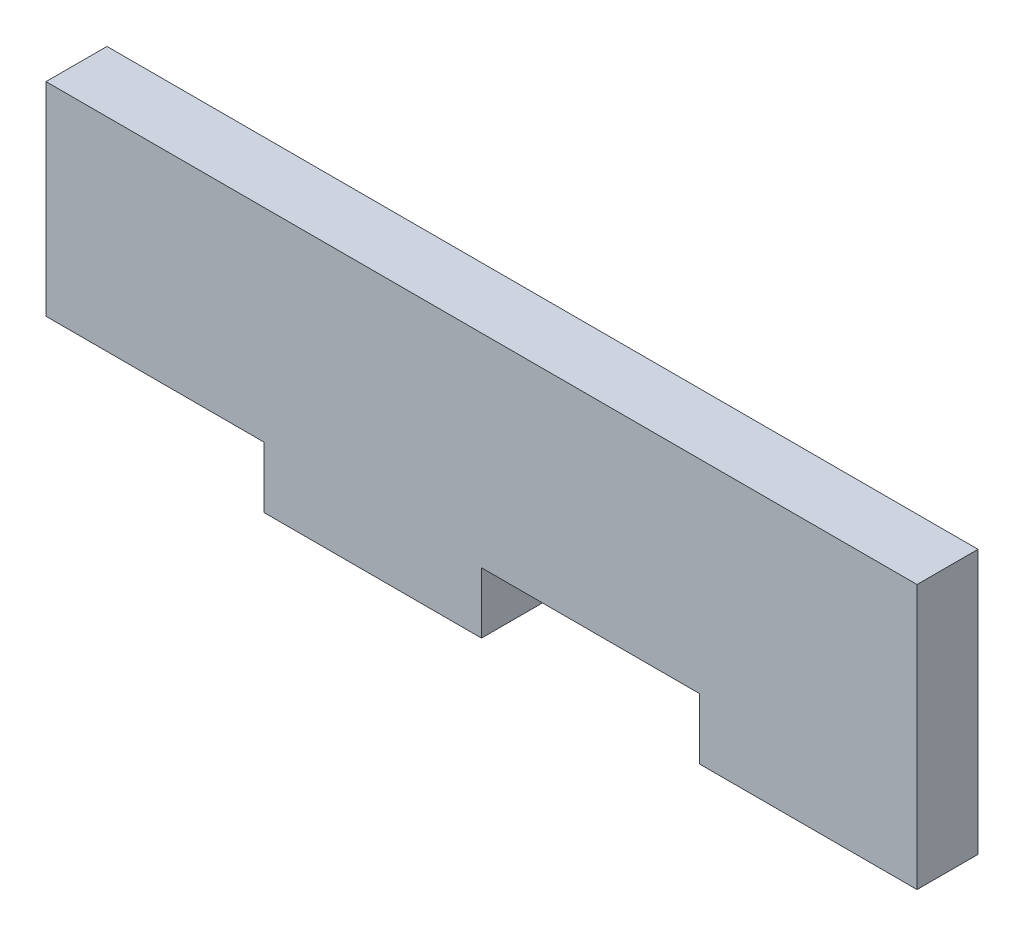
SolidWorks part; units mm, degrees
ref_plane "Front Plane" through (0, 0, 0) normal (0, 0, 1) x (1, 0, 0)
ref_plane "Top Plane" through (0, 0, 0) normal (0, 1, 0) x (1, 0, 0)
ref_plane "Right Plane" through (0, 0, 0) normal (1, 0, 0) x (0, 0, -1)
sketch "Sketch1" plane through (0, 0, 0) normal (0, 0, 1) x (1, 0, 0)
  line L1 (-382.8807, 285.7457) -> (-306.6807, 285.7457)
  line L2 (-382.8807, 285.7457) -> (-382.8807, 262.6317)
  line L3 (-382.8807, 262.6317) -> (-306.6807, 262.6317)
  line L4 (-306.6807, 285.7457) -> (-306.6807, 262.6317)
  dimension "D1" = 76.2
  dimension "D2" = 23.114
extrude "Boss-Extrude1" add sketch "Sketch1" along normal blind 5.334
sketch "Sketch2" plane through (0, 0, 5.334) normal (0, 0, 1) x (1, 0, 0)
  line L0 (-382.8807, 262.6317) -> (-306.6807, 262.6317) construction
  line L1 (-382.8807, 262.6317) -> (-363.8307, 262.6317)
  line L2 (-382.8807, 262.6317) -> (-382.8807, 267.9657)
  line L3 (-382.8807, 267.9657) -> (-363.8307, 267.9657)
  line L4 (-363.8307, 262.6317) -> (-363.8307, 267.9657)
  line L5 (-344.7807, 262.6317) -> (-325.7307, 262.6317)
  line L6 (-344.7807, 262.6317) -> (-344.7807, 267.9657)
  line L7 (-344.7807, 267.9657) -> (-325.7307, 267.9657)
  line L8 (-325.7307, 262.6317) -> (-325.7307, 267.9657)
  line L9 (-363.8307, 267.9657) -> (-344.7807, 267.9657) construction
  line L10 (-325.7307, 267.9657) -> (-306.6807, 267.9657) construction
  line L11 (-306.6807, 262.6317) -> (-306.6807, 285.7457) construction
  dimension "D1" = 5.334
extrude "Cut-Extrude1" cut sketch "Sketch2" against normal through all
equation "\"MDF\"= .21in"
equation "\"Foamcore\"= .13in"
equation "\"Gmaterial\"= \"MDF\""
equation "\"D1@Boss-Extrude1\"=\"MDF\""
equation "\"D1@Sketch2\"=\"MDF\""
equation "\"D2@Sketch1\"=\"MDF\"+0.7"
